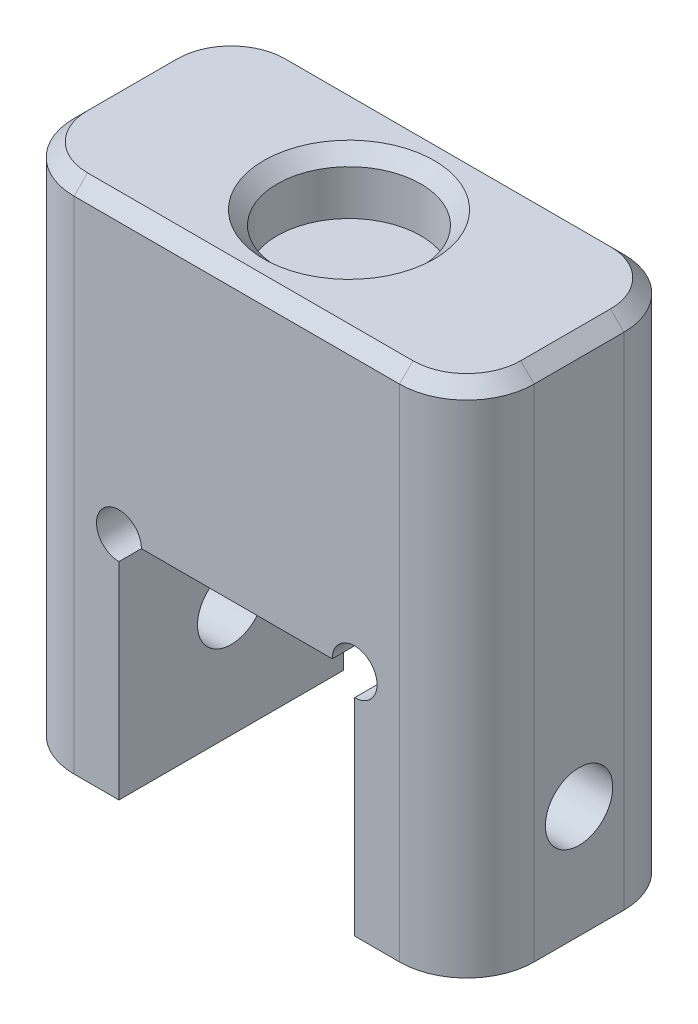
SolidWorks part; units mm, degrees
material "ﾎﾟﾘｴｽﾃﾙ樹脂"
ref_plane "正面" through (0, 0, 0) normal (0, 0, 1) x (1, 0, 0)
ref_plane "平面" through (0, 0, 0) normal (0, 1, 0) x (1, 0, 0)
ref_plane "右側面" through (0, 0, 0) normal (1, 0, 0) x (0, 0, -1)
sketch "ｽｹｯﾁ1" plane through (0, 0, 0) normal (0, 0, 1) x (1, 0, 0)
  line L0 (0, 11.45) -> (0, -11.45) construction
  line L1 (-10.25, -11.45) -> (10.25, -11.45)
  line L2 (-10.25, -11.45) -> (-10.25, 11.45)
  line L3 (-10.25, 11.45) -> (10.25, 11.45)
  line L4 (10.25, -11.45) -> (10.25, 11.45)
  line L5 (-10.25, -11.45) -> (10.25, 11.45) construction
  line L6 (-10.25, 11.45) -> (10.25, -11.45) construction
  line L8 (-5.25, -1.25) -> (5.25, -1.25)
  line L9 (-5.25, -1.25) -> (-5.25, -11.45)
  line L10 (-5.25, -11.45) -> (5.25, -11.45)
  line L11 (5.25, -1.25) -> (5.25, -11.45)
  line L12 (-5.25, -1.25) -> (5.25, -11.45) construction
  line L13 (-5.25, -11.45) -> (5.25, -1.25) construction
  point P0 (0, 0)
  point P7 (0, -6.35)
  dimension "D1" = 10.2
  dimension "D2" = 5
  dimension "D3" = 12.7
  dimension "D4" = 10.5
extrude "ﾎﾞｽ - 押し出し1" add sketch "ｽｹｯﾁ1" along normal blind 10 contours L8 L11 L1 L4 L3 L2 L9
sketch "ｽｹｯﾁ2" plane through (0, 11.45, 0) normal (0, 1, 0) x (1, 0, 0)
  line L0 (0, 0) -> (0, -10) construction
  line L1 (-10.25, -10) -> (10.25, -10) construction
  circle A0 centre (0, -5) radius 3.2
  dimension "D1" = 6.4
extrude "ｶｯﾄ - 押し出し1" cut sketch "ｽｹｯﾁ2" against normal blind 2.6
sketch "ｽｹｯﾁ3" plane through (10.25, 0, 0) normal (1, 0, 0) x (0, 0, -1)
  line L0 (-5, 11.45) -> (-5, -11.45) construction
  line L1 (-10, 11.45) -> (0, 11.45) construction
  line L2 (-10, -11.45) -> (0, -11.45) construction
  circle A0 centre (-5, -6.45) radius 1.5
  dimension "D1" = 5
  dimension "D2" = 3
extrude "ｶｯﾄ - 押し出し2" cut sketch "ｽｹｯﾁ3" against normal through all
sketch "ｽｹｯﾁ4" plane through (0, 0, 10) normal (0, 0, 1) x (1, 0, 0)
  circle A0 centre (5.25, -1.25) radius 1
  circle A1 centre (-5.25, -1.25) radius 1
  dimension "D1" = 2
extrude "ｶｯﾄ - 押し出し3" cut sketch "ｽｹｯﾁ4" against normal through all
fillet "ﾌｨﾚｯﾄ1" radius 3 4 edges at (-10.25, 0, 0) (-10.25, 0, 10) (10.25, 0, 0) (10.25, 0, 10)
chamfer "面取り1" distance 0.6 angle 45 9 edges at (9.3713, 11.45, 0.8787) (10.25, 11.45, 5) (9.3713, 11.45, 9.1213) (0, 11.45, 10) (-9.3713, 11.45, 9.1213) (-10.25, 11.45, 5) (-9.3713, 11.45, 0.8787) (0, 11.45, 0) (-3.2, 11.45, 5)
